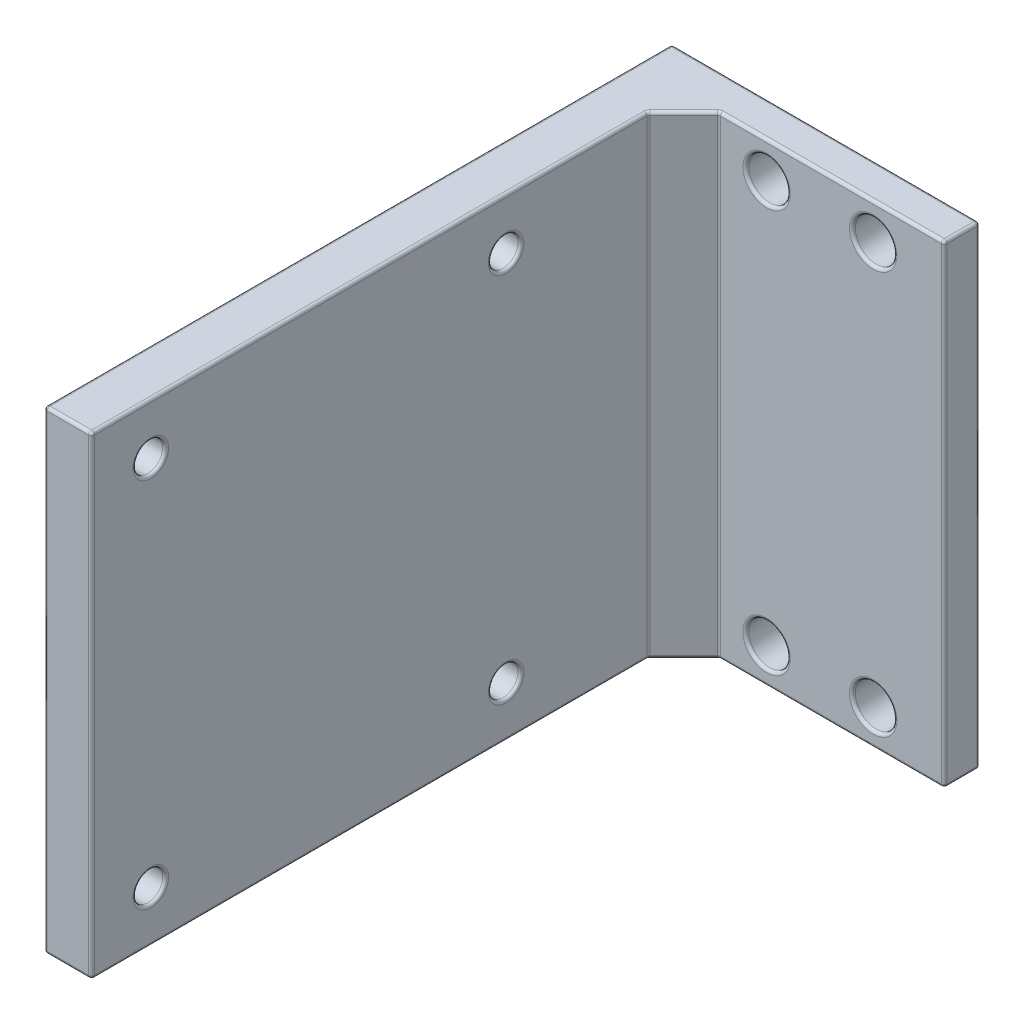
SolidWorks part; units mm, degrees
ref_plane "Front Plane" through (0, 0, 0) normal (1, 0, 0) x (0, 1, 0)
ref_plane "Top Plane" through (0, 0, 0) normal (0, 0, 1) x (0, 1, 0)
ref_plane "Right Plane" through (0, 0, 0) normal (0, 1, 0) x (-1, 0, 0)
sketch "Sketch1" plane through (0, 0, 0) normal (0, 0, 1) x (0, 1, 0)
  line L1 (-20, 20) -> (20, 20)
  line L2 (-20, 20) -> (-20, -6)
  line L3 (-20, -6) -> (20, -6)
  line L4 (20, 20) -> (20, -6)
  circle A0 centre (-17, 0) radius 1.75
  circle A1 centre (17, 0) radius 1.75
  circle A2 centre (17, 9) radius 1.75
  circle A3 centre (-17, 9) radius 1.75
  point P0 (0, 0)
  point P8 (0, 0)
  dimension "D3" = 3.5
  dimension "D1" = 40
  dimension "D2" = 26
  dimension "D4" = 17
  dimension "D7" = 6
  dimension "D8" = 20
  dimension "D9" = 17
  dimension "D10" = 9
  dimension "D5" = 2
  dimension "D6" = 2
extrude "Boss-Extrude1" add sketch "Sketch1" along normal blind 3
sketch "Sketch2" plane through (0, 0, 3) normal (0, 0, 1) x (1, 0, 0)
  line L0 (-20, -20) -> (6, -20) construction
  line L1 (-20, 20) -> (-16, 20)
  line L2 (-20, 20) -> (-20, -20)
  line L3 (-20, -20) -> (-16, -20)
  line L4 (-16, 20) -> (-16, -20)
  dimension "D1" = 4
extrude "Boss-Extrude2" add sketch "Sketch2" along normal blind 50
sketch "Sketch3" plane through (-20, 0, 0) normal (-1, 0, 0) x (0, -1, 0)
  line L0 (-20, 53) -> (20, 53) construction
  line L1 (-20, 53) -> (-20, 0) construction
  line L3 (20, 53) -> (20, 0) construction
  circle A0 centre (-15.7, 48) radius 1.25
  circle A1 centre (15.7, 48) radius 1.25
  circle A2 centre (15.7, 18) radius 1.25
  circle A3 centre (-15.7, 18) radius 1.25
  dimension "D1" = 2.5
  dimension "D2" = 5
  dimension "D5" = 4.3
  dimension "D6" = 4.3
  dimension "D7" = 18
  dimension "D3" = 2
  dimension "D4" = 2
extrude "Cut-Extrude1" cut sketch "Sketch3" against normal blind 50
chamfer "Chamfer1" distance 3 angle 45 1 edges at (-16, 0, 3)
fillet "Fillet2" radius 0.25 37 edges at (-20, 15.7, 19.25) (-20, -15.7, 19.25) (-20, -15.7, 49.25) (-20, 15.7, 49.25) (-16, 14.45, 48) (-16, -16.95, 48) (-16, -16.95, 18) (-16, 14.45, 18) (-20, 0, 53) (-18, -20, 53) (-16, 0, 53) (-18, 20, 53) (-16, 20, 29.5) (-16, -20, 29.5) (-7.25, -17, 0) (-7.25, -17, 3) (-7.25, 17, 0) (-7.25, 17, 3) (1.75, 17, 0) (1.75, 17, 3) (1.75, -17, 0) (1.75, -17, 3) (-7, 20, 0) (-20, 0, 0) (-7, -20, 0) (6, 0, 0) (-3.5, 20, 3) (-3.5, -20, 3) (6, 0, 3) (6, 20, 1.5) (6, -20, 1.5) (-20, -20, 26.5) (-20, 20, 26.5) (-16, 0, 6) (-13, 0, 3) (-14.5, 20, 4.5) (-14.5, -20, 4.5)
